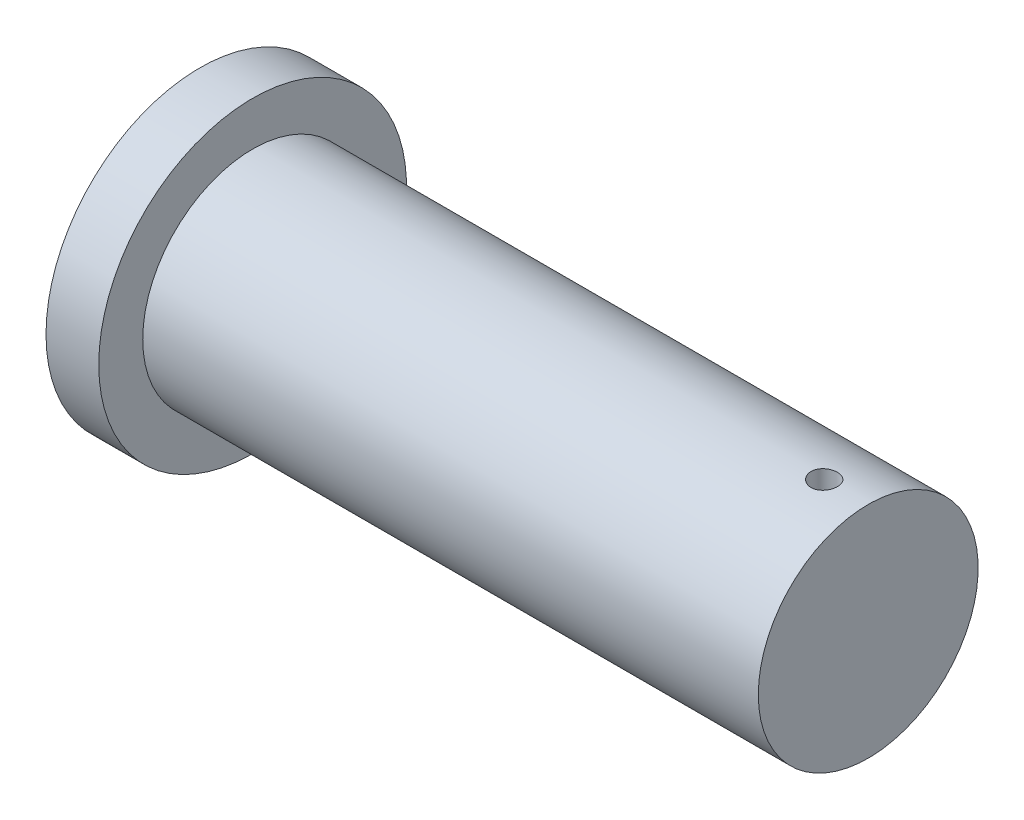
SolidWorks part; units mm, degrees
ref_plane "Front Plane" through (0, 0, 0) normal (0, 0, 1) x (1, 0, 0)
ref_plane "Top Plane" through (0, 0, 0) normal (0, 1, 0) x (1, 0, 0)
ref_plane "Right Plane" through (0, 0, 0) normal (1, 0, 0) x (0, 0, -1)
sketch "Sketch1" plane through (0, 0, 0) normal (0, 0, 1) x (1, 0, 0)
  line L0 (0, 0) -> (0, 250)
  line L1 (0, 250) -> (-1400, 250)
  line L2 (-1400, 250) -> (-1400, 350)
  line L3 (-1400, 350) -> (-1520, 350)
  line L4 (-1520, 350) -> (-1520, 0)
  line L5 (-1520, 0) -> (0, 0)
  dimension "D1" = 250
  dimension "D2" = 350
  dimension "D3" = 120
  dimension "D4" = 1520
revolve "Revolve1" add sketch "Sketch1" angle 360 about L5
sketch "Sketch2" plane through (0, 0, 0) normal (0, 1, 0) x (1, 0, 0)
  line L0 (-1400, -350) -> (-1400, 350) construction
  circle A0 centre (-100, 0) radius 30
  dimension "D1" = 60
  dimension "D2" = 1300
extrude "Cut-Extrude1" cut sketch "Sketch2" against normal through all both and the other way through all
